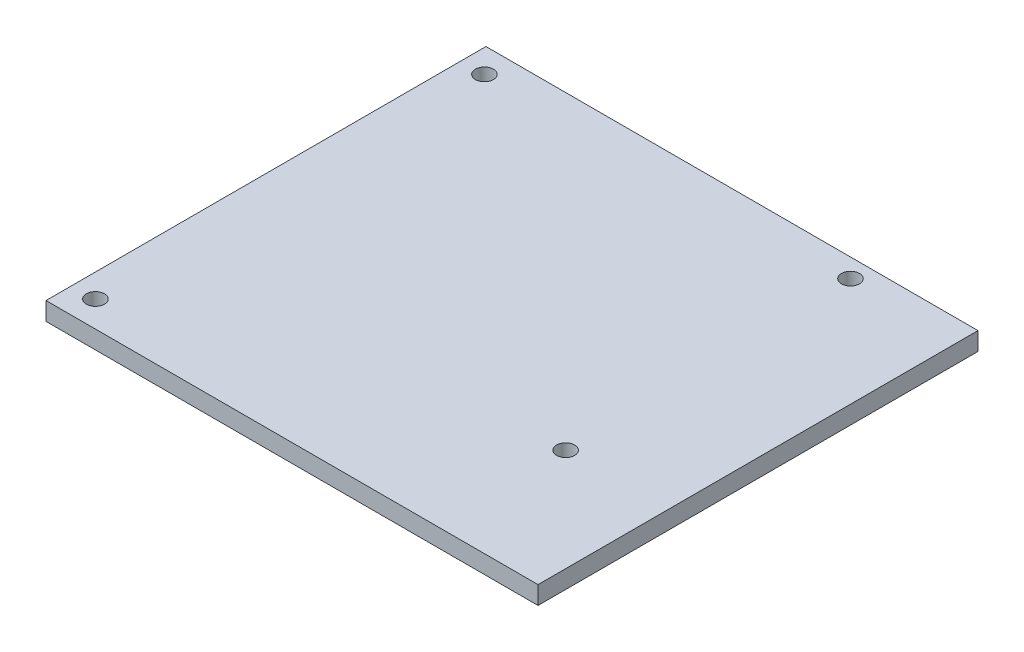
SolidWorks part; units mm, degrees
ref_plane "前视基准面" through (0, 0, 0) normal (0, 0, 1) x (1, 0, 0)
ref_plane "上视基准面" through (0, 0, 0) normal (0, 1, 0) x (1, 0, 0)
ref_plane "右视基准面" through (0, 0, 0) normal (1, 0, 0) x (0, 0, -1)
sketch "草图1" plane through (0, 0, 0) normal (0, 1, 0) x (1, 0, 0)
  line L0 (1.7, 15.1419) -> (1.7, 13.9998) construction
  line L1 (-7.176, -16.51) -> (74.421, -16.51)
  line L2 (-7.176, -16.51) -> (-7.176, 56.452)
  line L3 (-7.176, 56.452) -> (74.421, 56.452)
  line L4 (74.421, -16.51) -> (74.421, 56.452)
  line L9 (1.2985, 14.6) -> (2.0408, 14.6) construction
  circle A0 centre (-3.302, -12.192) radius 1.5
  circle A1 centre (-3.302, 52.324) radius 1.5
  circle A2 centre (56.388, 53.34) radius 1.5
  circle A3 centre (57.404, 5.08) radius 1.5
  dimension "D13" = 3
  dimension "D14" = 3
  dimension "D15" = 3
  dimension "D16" = 3
  dimension "D1" = 72.962
  dimension "D2" = 81.597
  dimension "D3" = 7.176
  dimension "D4" = 16.51
  dimension "D5" = 3.302
  dimension "D6" = 12.192
  dimension "D7" = 3.302
  dimension "D8" = 52.324
  dimension "D9" = 57.404
  dimension "D10" = 5.08
  dimension "D11" = 53.34
  dimension "D12" = 56.388
  dimension "D20" = 1.7
  dimension "D21" = 14.6
extrude "凸台-拉伸1" add sketch "草图1" along normal blind 3
